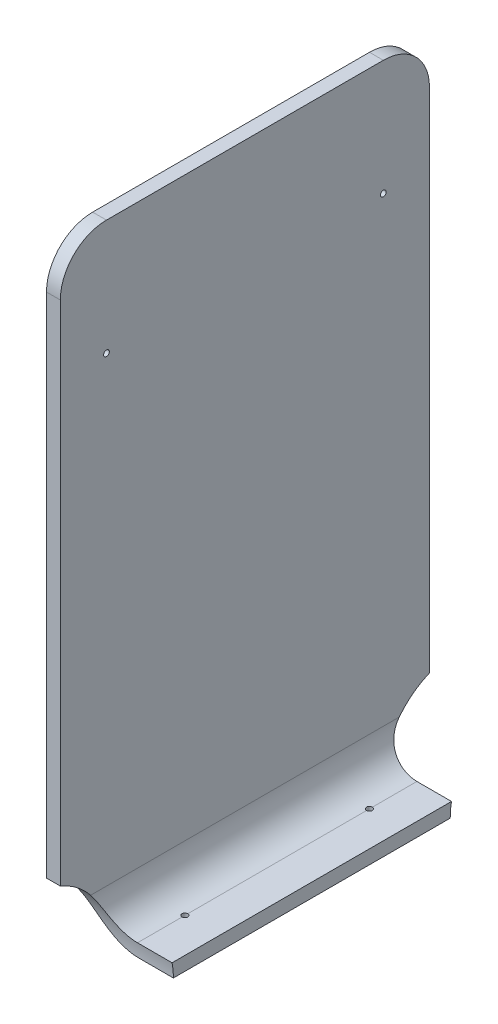
SolidWorks part; units mm, degrees
ref_plane "Front Plane" through (0, 0, 0) normal (0, 0, 1) x (1, 0, 0)
ref_plane "Top Plane" through (0, 0, 0) normal (0, 1, 0) x (1, 0, 0)
ref_plane "Right Plane" through (0, 0, 0) normal (1, 0, 0) x (0, 0, -1)
sketch "Sketch1" plane through (0, 0, 0) normal (0, 0, 1) x (1, 0, 0)
  line L0 (0, 0) -> (-19.05, 0)
  line L1 (-44.45, 25.4) -> (-44.45, 342.9)
  arc A0 (-19.05, 0) -> (-44.45, 25.4) centre (-19.05, 25.4) cw
extrude "Extrude-Thin1" add sketch "Sketch1" along normal mid plane 203.2 thin
fillet "Fillet1" radius 25.4 1 edges at (-40.64, 342.9, 101.6)
fillet "Fillet2" radius 25.4 1 edges at (-40.64, 342.9, -101.6)
sketch3d "3DSketch1"
  point P0 (0, 3.4181, 29.6445)
sketch3d "3DSketch2"
  point P0 (0, 4.0614, -8.6423)
ref_plane "Front Plane on End" through (0, 0, 0) normal (1, 0, 0) x (0, 0, -1)
sketch "Sketch2" plane through (0, 0, 0) normal (1, 0, 0) x (0, 0, -1)
  line L0 (-101.6, 0) -> (-76.2, 0)
  line L1 (-101.6, 0) -> (101.6, 0) construction
  line L2 (-101.6, 0) -> (-101.6, 38.1)
  line L3 (101.6, 0) -> (101.6, 38.1)
  line L4 (101.6, 0) -> (76.2, 0)
  arc A0 (-76.2, 0) -> (-101.6, 38.1) centre (-117.475, 0) ccw
  arc A1 (76.2, 0) -> (101.6, 38.1) centre (117.475, 0) cw
extrude "Cut-Extrude1" cut sketch "Sketch2" against normal blind 67.818 and the other way blind 15.494
sketch3d "3DSketch3"
  point P0 (-36.83, 256.4124, 10.5401)
ref_plane "Plane1" through (-36.83, 0, 0) normal (1, 0, 0) x (0, 0, -1)
sketch "Sketch3" plane through (-36.83, 0, 0) normal (1, 0, 0) x (0, 0, -1)
  circle A0 centre (-76.2, 279.4) radius 1.5875
  circle A1 centre (76.2, 279.4) radius 1.5875
extrude "Cut-Extrude2" cut sketch "Sketch3" against normal blind 16.51 and the other way blind 20.32
sketch3d "3DSketch4"
  point P0 (0, 3.5145, -29.0381)
sketch "Sketch4" plane through (0, 7.62, 0) normal (0, 1, 0) x (1, 0, 0)
  line L1 (-19.05, -76.9095) -> (-19.05, 76.9095) construction
  circle A0 centre (-19.05, -50.8) radius 1.5875
  circle A1 centre (-19.05, 50.8) radius 1.5875
extrude "Cut-Extrude3" cut sketch "Sketch4" against normal blind 22.86 and the other way blind 14.732
